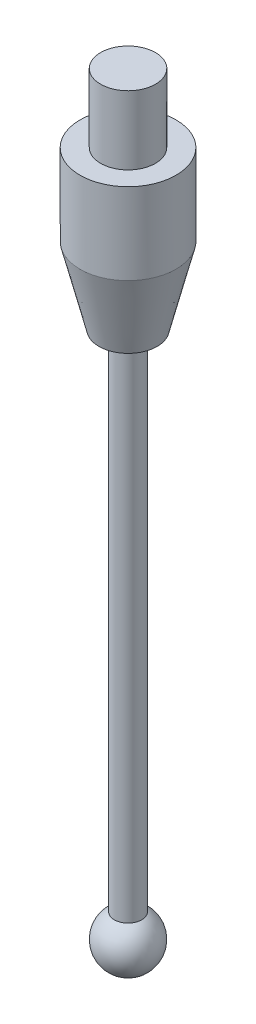
SolidWorks part; units mm, degrees
ref_plane "Front" through (0, 0, 0) normal (0, 0, 1) x (1, 0, 0)
ref_plane "Top" through (0, 0, 0) normal (0, 1, 0) x (1, 0, 0)
ref_plane "Right" through (0, 0, 0) normal (1, 0, 0) x (0, 0, -1)
sketch "Sketch2" plane through (0, 0, 0) normal (0, 0, 1) x (1, 0, 0)
  line L0 (0, 0) -> (0, 50.6183) construction
  line L1 (1, 1.7321) -> (1, 38.5)
  line L2 (0, 0) -> (0, -2) construction
  line L3 (1, 38.5) -> (2.1231, 38.5)
  line L4 (2.1231, 38.5) -> (3.5, 44.0686)
  line L5 (3.5, 44.0686) -> (3.5, 50)
  line L6 (3.5, 50) -> (0, 50)
  line L7 (0, -2) -> (0, 50)
  circle A0 centre (0, 0) radius 2 construction
  arc A1 (0, -2) -> (1, 1.7321) centre (0, 0) ccw
  dimension "D1" = 4
  dimension "D3" = 38.5
  dimension "D2" = 2
  dimension "D4" = 7
  dimension "D5" = 50
revolve "Revolve1" add sketch "Sketch2" angle 360 about L7
sketch "Sketch3" plane through (0, 50, 0) normal (0, 1, 0) x (1, 0, 0)
  circle A0 centre (0, 0) radius 2
  dimension "D1" = 4
extrude "Boss-Extrude1" add sketch "Sketch3" along normal blind 5
